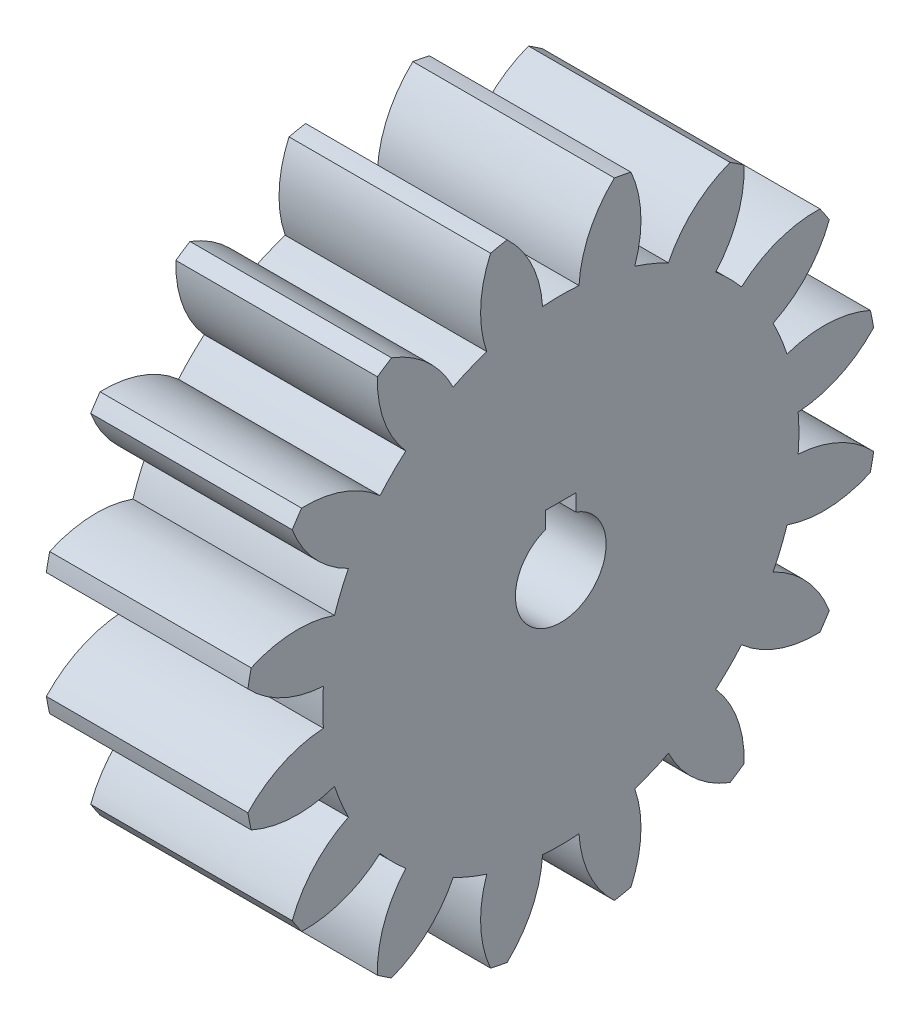
SolidWorks part; units mm, degrees
ref_plane "Plane1" through (0, 0, 0) normal (0, 0, 1) x (1, 0, 0)
ref_plane "Plane2" through (0, 0, 0) normal (0, 1, 0) x (1, 0, 0)
ref_plane "Plane3" through (0, 0, 0) normal (1, 0, 0) x (0, 0, -1)
other "Configuration Table"
sketch "HoldingSke" plane through (0, 0, 0) normal (0, 1, 0) x (1, 0, 0)
  line L0 (0, 0) -> (0.1373, -0.0394)
  line L1 (-15, 0) -> (100, 0) construction
  line L2 (0, 0) -> (-2.1039, 2.3779)
  line L3 (0, 0) -> (-11.863, 4.5341)
  line L4 (0, 0) -> (8.3015, 2.3804)
  line L5 (0, 0) -> (-46.8476, -17.4728)
  line L6 (0, 0) -> (-33.1585, -22.3721)
  line L7 (-2.1039, 2.3779) -> (8.6586, 51.2059)
  line L8 (-76.2, 54.61) -> (-73.4, 54.61)
  line L9 (-71.009, 38.7566) -> (-53.1078, 45.2721)
  line L10 (-76.2, 71.12) -> (104.1128, 71.12)
  line L11 (0, 0) -> (-40, 0)
  line L12 (-76.2, 101.6) -> (-75.969, 101.6)
  line L13 (24.9733, 27.94) -> (52.9518, 28.4284)
  line L14 (24.9733, 27.94) -> (24.9743, 27.94)
  line L15 (24.9733, 27.94) -> (100.4006, 29.5858)
  line L16 (-63.627, -7) -> (-12.827, -7)
  circle A0 centre (0, 0) radius 9
  circle A1 centre (0, 0) radius 37.5
  circle A2 centre (0, 0) radius 37.5
  circle A3 centre (0, 0) radius 9
  dimension "MHD" = 75
  dimension "Hub_dia" = 75
  dimension "Bore" = 18
  dimension "MBD" = 18
  dimension "Num_teeth" = 16
  dimension "Pitch" = 0.1429
  dimension "Overall_len" = 50
  dimension "Show_teeth" = 16
  dimension "Thickness" = 40
  dimension "OAL" = 50.0001
  dimension "T_dim" = 2.8
  dimension "Ap" = 20
  dimension "H" = 19.05
  dimension "Pitch_radius" = 180.3128
  dimension "Width" = 40
  dimension "Backlash" = 0.231
  dimension "Addendum_fac" = 1
  dimension "Dedendum_fac" = 1.25
  dimension "Clearance_fac" = 0.25
  dimension "Dedendum_add" = 0.001
  dimension "Module" = 7
sketch "BasProSke" plane through (0, 0, 0) normal (0, 1, 0) x (1, 0, 0)
  line L0 (-10, 0) -> (60, 0) construction
  line L1 (0, 0) -> (0, 63)
  line L2 (0, 0) -> (40, 0)
  line L3 (40, 0) -> (40, 63)
  line L4 (40, 63) -> (0, 63)
  dimension "Thickness" = 40
  dimension "Diameter" = 126
revolve "Base-Revolve" add sketch "BasProSke" angle 360 about L0
sketch "TooCutSke" plane through (0, 0, 0) normal (1, 0, 0) x (0, 0, -1)
  line L1 (0, 0) -> (0, 107) construction
  line L2 (0, 0) -> (-5.8929, 55.6891) construction
  line L3 (0, 0) -> (-21.7599, 109.3942) construction
  line L4 (-5.8929, 55.6891) -> (-10.8799, 54.6971) construction
  arc A0 (3.6152, 47.1105) -> (-3.6152, 47.1105) centre (0, 0) ccw
  arc A1 (10.6647, 62.1166) -> (-10.6647, 62.1166) centre (0, 0) ccw
  circle A2 centre (0, 0) radius 56 construction
  circle A3 centre (0, 0) radius 52.6228 construction
  arc A4 (-3.6152, 47.1105) -> (-10.6647, 62.1166) centre (-25.9748, 45.7654) ccw
  arc A5 (10.6647, 62.1166) -> (3.6152, 47.1105) centre (25.9748, 45.7654) ccw
  dimension "Root_dia" = 94.498
  dimension "Overcut_dia" = 126.0508
  dimension "Pitch_dia" = 112
  dimension "Base_dia" = 105.2456
  dimension "Flank_rad" = 22.4
  dimension "Half_ang" = 11.25
  dimension "Half_CT" = 5.0847
extrude "ToothCut" cut sketch "TooCutSke" along normal through all
fillet "Breaks" [suppressed] radius 0.14
fillet "RootFillets" [suppressed] radius 1.751
pattern_circular "TeethCuts" count 16 every 22.5 about axis through (-10, 0, 0) along (1, 0, 0) of "ToothCut", "RootFillets", "Breaks"
sketch "HubNeaOneSke" plane through (0, 0, 0) normal (-1, 0, 0) x (0, 0, 1)
  circle A0 centre (0, 0) radius 37.5
  dimension "Diameter" = 75
extrude "HubNearOne" [suppressed] add sketch "HubNeaOneSke" along normal blind 10.0001
sketch "HubNeaBotSke" plane through (0, 0, 0) normal (-1, 0, 0) x (0, 0, 1)
  circle A0 centre (0, 0) radius 37.5
  dimension "Diameter" = 75
extrude "HubNearBoth" [suppressed] add sketch "HubNeaBotSke" along normal blind 5
ref_plane "FarPln" through (40, 0, 0) normal (1, 0, 0) x (0, 0, -1)
sketch "HubFarSke" plane through (40, 0, 0) normal (1, 0, 0) x (0, 0, -1)
  circle A0 centre (0, 0) radius 37.5
  dimension "Diameter" = 75
extrude "HubFar" [suppressed] add sketch "HubFarSke" along normal blind 5
sketch "BorSke" plane through (0, 0, 0) normal (1, 0, 0) x (0, 0, -1)
  circle A0 centre (0, 0) radius 9
  dimension "Diameter" = 18
extrude "Bore" cut sketch "BorSke" along normal mid plane 100.0001
sketch "KeySke" plane through (0, 0, 0) normal (1, 0, 0) x (0, 0, -1)
  line L0 (-3, 0) -> (-3, 11.8)
  line L1 (-3, 11.8) -> (3, 11.8)
  line L2 (3, 11.8) -> (3, 0)
  line L3 (0, 0) -> (0, 34) construction
  line L4 (-3, 0) -> (3, 0)
  dimension "Offset" = 11.8
  dimension "Width" = 6
extrude "Keyway" cut sketch "KeySke" along normal mid plane 100.0001
pattern_circular "Keyway2" [suppressed] count 2 every 90 about axis through (-10, 0, 0) along (1, 0, 0)
equation "' \"Module@HoldingSke\" = 6.35"
equation "' \"Num_teeth@HoldingSke\" = 12"
equation "' \"Ap@HoldingSke\" =  20"
equation "' \"Ap@HoldingSke\" = 20"
equation "' \"Width@HoldingSke\" = 0.5 * 25.4"
equation "' \"Hub_dia@HoldingSke\"= 1 * 25.4"
equation "' \"Hub_dia@HoldingSke\" = 1 * 25.4"
equation "' \"Overall_len@HoldingSke\" = 1.0 * 25.4"
equation "' \"Bore@HoldingSke\" = 0.75 * 25.4"
equation "' \"T_dim@HoldingSke\" = 0.1 * 25.4"
equation "' \"Width@KeySke\" = 0.25 * 25.4"
equation "' \"Show_teeth@HoldingSke\" = 13"
equation "' \"Backlash@HoldingSke\" = 0.009 * 25.4"
equation "' \"Addendum_fac@HoldingSke\" = 1.0"
equation "' \"Dedendum_fac@HoldingSke\" = 1.25"
equation "' \"Dedendum_add@HoldingSke\" = 0.00005 * 25.4"
equation "' \"Clearance_fac@HoldingSke\" = 0.25"
equation "\"Pitch@HoldingSke\" = 1 / \"Module@HoldingSke\""
equation "\"Overcut_dia@TooCutSke\" = (\"Num_teeth@HoldingSke\" + 2 * \"Addendum_fac@HoldingSke\") / \"Pitch@HoldingSke\" + 0.002 * 25.4"
equation "\"Pitch_dia@TooCutSke\" = \"Num_teeth@HoldingSke\" / \"Pitch@HoldingSke\""
equation "\"Base_dia@TooCutSke\" = \"Num_teeth@HoldingSke\" / \"Pitch@HoldingSke\" * cos((\"Ap@HoldingSke\"  * 3.14159265 / 180))"
equation "\"Root_dia@TooCutSke\" = (\"Num_teeth@HoldingSke\" + 2) / \"Pitch@HoldingSke\" - 2 * (\"Addendum_fac@HoldingSke\" + \"Dedendum_fac@HoldingSke\") / \"Pitch@HoldingSke\" - \"Dedendum_add@HoldingSke\" * 2"
equation "\"Half_ang@TooCutSke\" = 180 / \"Num_teeth@HoldingSke\""
equation "\"Half_CT@TooCutSke\" = \"Num_teeth@HoldingSke\" / \"Pitch@HoldingSke\" * sin((3.14159265 / 2 / \"Num_teeth@HoldingSke\")) / 2 - 7 * \"Backlash@HoldingSke\" / 4"
equation "\"Flank_rad@TooCutSke\" = \"Num_teeth@HoldingSke\" / \"Pitch@HoldingSke\" / 5"
equation "\"Radius@RootFillets\" = \"Clearance_fac@HoldingSke\" / \"Pitch@HoldingSke\" + \"Dedendum_add@HoldingSke\""
equation "\"Break_rad@Breaks\" = 0.02 / \"Pitch@HoldingSke\""
equation "\"Thickness@HoldingSke\" = \"Width@HoldingSke\""
equation "\"OAL@HoldingSke\" = \"Thickness@HoldingSke\""
equation "\"MHD@HoldingSke\" = (\"Num_teeth@HoldingSke\" + 2) / \"Pitch@HoldingSke\" - 2 * (\"Addendum_fac@HoldingSke\" + \"Dedendum_fac@HoldingSke\")  / \"Pitch@HoldingSke\" - \"Dedendum_add@HoldingSke\" * 2"
equation "\"MBD@HoldingSke\" = (\"Num_teeth@HoldingSke\" + 2) / \"Pitch@HoldingSke\" - 2 * (\"Addendum_fac@HoldingSke\" + \"Dedendum_fac@HoldingSke\")  / \"Pitch@HoldingSke\" - \"Dedendum_add@HoldingSke\" * 2 - 0.002 * 25.4"
equation "\"MHD@HoldingSke\" = ((sgn( \"MHD@HoldingSke\" - \"Hub_dia@HoldingSke\" )-1)*( \"MHD@HoldingSke\" - \"Hub_dia@HoldingSke\" ))/-2+ \"Hub_dia@HoldingSke\""
equation "\"MBD@HoldingSke\" = ((sgn( \"MBD@HoldingSke\" - \"Bore@HoldingSke\" )-1)*( \"MBD@HoldingSke\" - \"Bore@HoldingSke\" ))/-2+ \"Bore@HoldingSke\""
equation "\"OAL@HoldingSke\" = ((sgn( \"OAL@HoldingSke\" - \"Overall_len@HoldingSke\" )+1)*( \"OAL@HoldingSke\" - \"Overall_len@HoldingSke\" ))/2 + \"Overall_len@HoldingSke\" + 0.000002 * 25.4"
equation "\"Num_teeth@TeethCuts\" = int( \"Show_teeth@HoldingSke\" ) + 1"
equation "\"Num_teeth@TeethCuts\" = ((sgn( \"Num_teeth@TeethCuts\" - \"Num_teeth@HoldingSke\" )-1)*( \"Num_teeth@TeethCuts\" - \"Num_teeth@HoldingSke\" ))/-2+ \"Num_teeth@HoldingSke\""
equation "\"Num_teeth@TeethCuts\" = ((sgn( \"Num_teeth@TeethCuts\" - 2.0)+1)*( \"Num_teeth@TeethCuts\" - 2.0))/2 +2.0"
equation "\"Angle@TeethCuts\" = 360.0 / \"Num_teeth@HoldingSke\""
equation "\"Diameter@BasProSke\" = (\"Num_teeth@HoldingSke\" + 2 * \"Addendum_fac@HoldingSke\") / \"Pitch@HoldingSke\""
equation "\"Thickness@BasProSke\"  = \"Thickness@HoldingSke\""
equation "' \"Fillet_rad@BasProSke\" =  \"Thickness@HoldingSke\" * 0.05"
equation "' \"Fillet_rad@BasProSke\" = \"Thickness@HoldingSke\" * 0.05"
equation "\"MHD@HoldingSke\" = ((sgn( \"MHD@HoldingSke\" - \"Root_dia@TooCutSke\" )-1)*( \"MHD@HoldingSke\" - \"Root_dia@TooCutSke\" ))/-2+ \"Root_dia@TooCutSke\""
equation "\"Diameter@HubNeaOneSke\" = \"MHD@HoldingSke\""
equation "\"Length@HubNearOne\" = \"OAL@HoldingSke\" - \"Thickness@BasProSke\""
equation "\"Diameter@HubNeaBotSke\" = \"MHD@HoldingSke\""
equation "\"Length@HubNearBoth\" = ( \"OAL@HoldingSke\" - \"Thickness@BasProSke\" ) / 2.0"
equation "\"Thickness@FarPln\" = \"Thickness@BasProSke\""
equation "\"Diameter@HubFarSke\" = \"MHD@HoldingSke\""
equation "\"Length@HubFar\" = ( \"OAL@HoldingSke\" - \"Thickness@BasProSke\" ) / 2.0"
equation "\"Diameter@BorSke\" = \"MBD@HoldingSke\""
equation "\"D1@Bore\" = \"OAL@HoldingSke\" * 2.0"
equation "\"D1@Keyway\" = \"OAL@HoldingSke\" * 2.0"
equation "\"Offset@KeySke\" = \"T_dim@HoldingSke\" + \"MBD@HoldingSke\" / 2.0"
